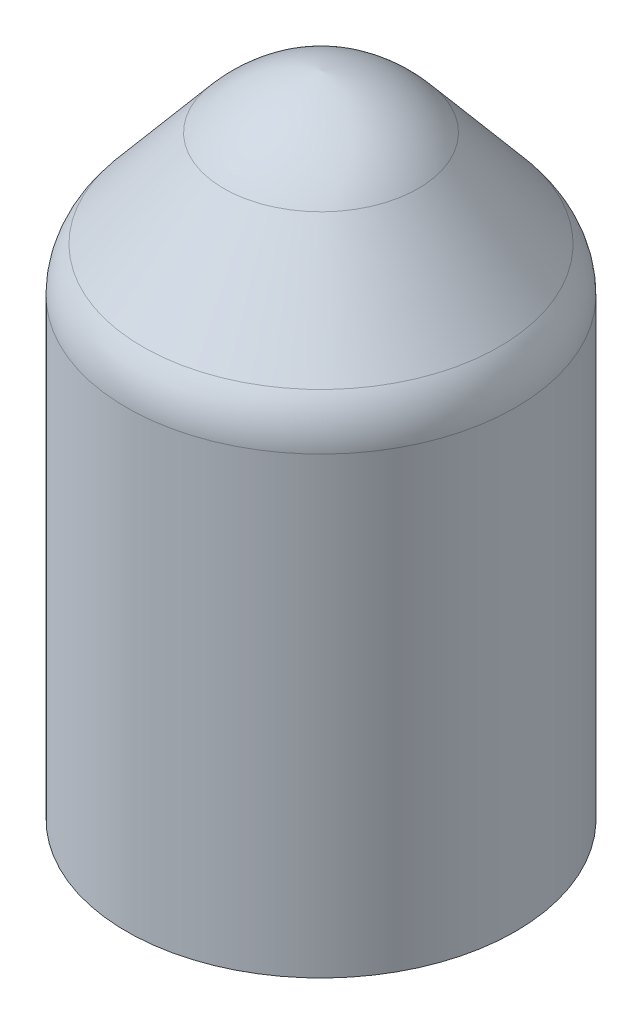
SolidWorks part; units mm, degrees
ref_plane "Front Plane" through (0, 0, 0) normal (0, 0, 1) x (1, 0, 0)
ref_plane "Top Plane" through (0, 0, 0) normal (0, 1, 0) x (1, 0, 0)
ref_plane "Right Plane" through (0, 0, 0) normal (1, 0, 0) x (0, 0, -1)
sketch "Sketch1" plane through (0, 0, 0) normal (0, 0, 1) x (1, 0, 0)
  line L1 (55, 153.7374) -> (30, 183.5312)
  line L2 (0, 200) -> (0, 140)
  line L3 (60, 140) -> (60, 0)
  line L4 (60, 0) -> (0, 0)
  line L5 (0, 0) -> (0, 140)
  arc A0 (60, 140) -> (55, 153.7374) centre (38.6284, 140) ccw
  arc A1 (30, 183.5312) -> (0, 200) centre (-6.1911, 153.1633) ccw
  point P4 (27.977, 188.2351)
  point P6 (30.783, 184.7292)
  point P10 (0, 0)
  dimension "D5" = 30
  dimension "D1" = 60
  dimension "D2" = 140
  dimension "D3" = 140
  dimension "D4" = 60
  dimension "D6" = 5
  dimension "D7" = 40
revolve "Revolve3" add sketch "Sketch1" angle 360 about L2
shell "Shell3" thickness 2
